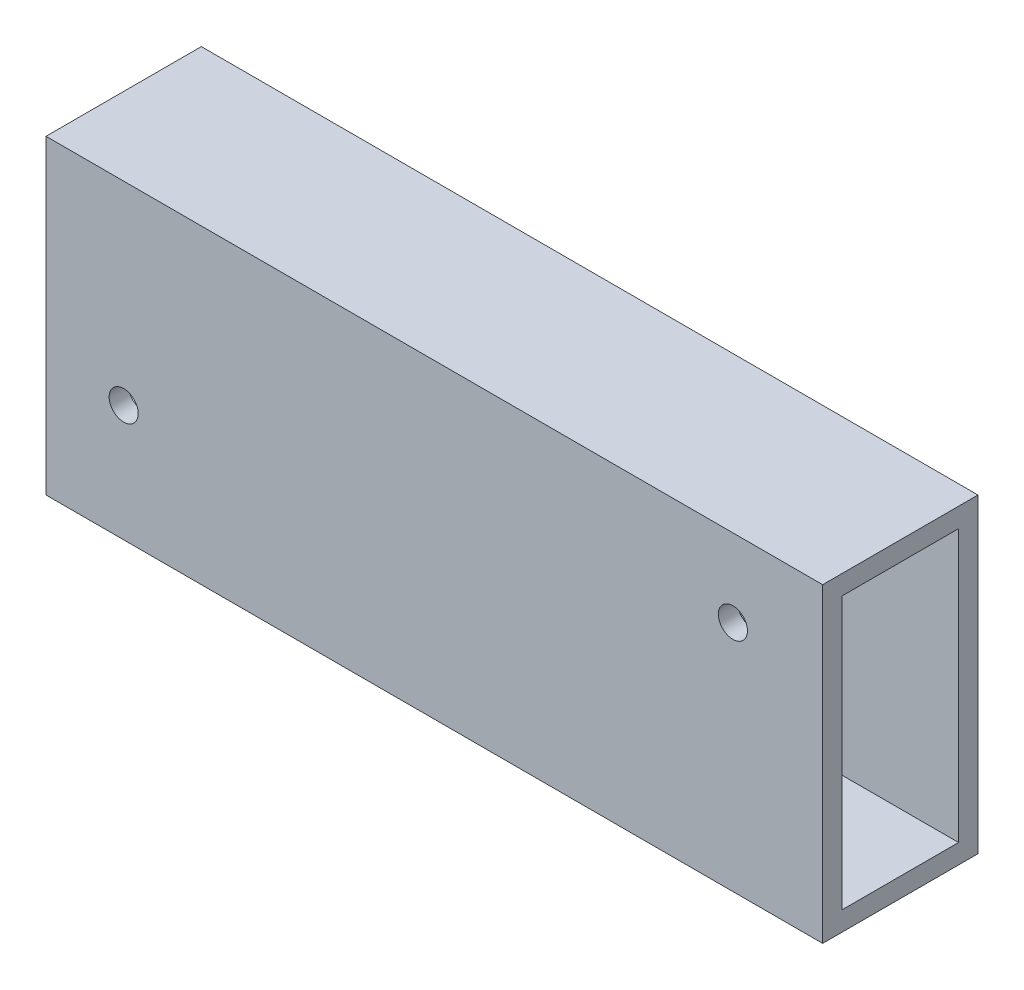
SolidWorks part; units mm, degrees
ref_plane "Front Plane" through (0, 0, 0) normal (0, 0, 1) x (1, 0, 0)
ref_plane "Top Plane" through (0, 0, 0) normal (0, 1, 0) x (1, 0, 0)
ref_plane "Right Plane" through (0, 0, 0) normal (1, 0, 0) x (0, 0, -1)
sketch "Sketch2" plane through (0, 0, 0) normal (1, 0, 0) x (0, 0, -1)
  line L0 (-10.4579, 20.5176) -> (8.5921, 20.5176)
  line L1 (-13.6329, 23.6926) -> (11.7671, 23.6926)
  line L2 (-13.6329, 23.6926) -> (-13.6329, -27.1074)
  line L3 (-13.6329, -27.1074) -> (11.7671, -27.1074)
  line L4 (11.7671, 23.6926) -> (11.7671, -27.1074)
  line L5 (8.5921, 20.5176) -> (8.5921, -23.9324)
  line L6 (-10.4579, -23.9324) -> (8.5921, -23.9324)
  line L7 (-10.4579, 20.5176) -> (-10.4579, -23.9324)
  dimension "D1" = 50.8
  dimension "D2" = 25.4
  dimension "D3" = 3.175
extrude "Boss-Extrude1" add sketch "Sketch2" along normal blind 127
sketch "Sketch4" plane through (0, 0, 13.6329) normal (0, 0, 1) x (1, 0, 0)
  line L0 (0, 23.6926) -> (0, -27.1074) construction
  line L1 (127, -27.1074) -> (0, -27.1074) construction
  line L2 (127, 23.6926) -> (0, 23.6926) construction
  circle A0 centre (12.7, -8.0574) radius 2.3813
  circle A1 centre (112.3202, 10.9926) radius 2.3813
  dimension "D1" = 12.7
  dimension "D3" = 101.4253
  dimension "D2" = 19.05
  dimension "D4" = 12.7
extrude "Cut-Extrude2" cut sketch "Sketch4" against normal blind 25.4
